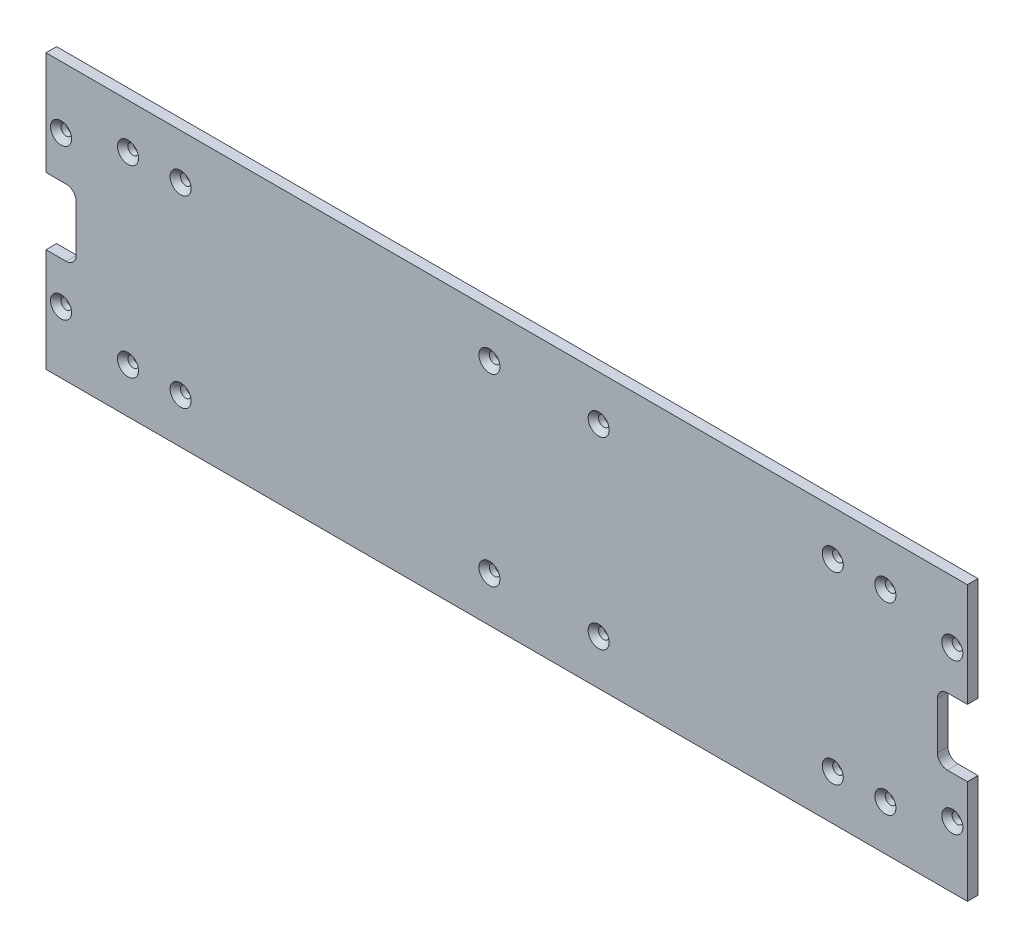
SolidWorks part; units mm, degrees
ref_plane "Plan de face" through (0, 0, 0) normal (0, 0, 1) x (1, 0, 0)
ref_plane "Plan de dessus" through (0, 0, 0) normal (0, 1, 0) x (1, 0, 0)
ref_plane "Plan de droite" through (0, 0, 0) normal (1, 0, 0) x (0, 0, -1)
sketch "Esquisse1" plane through (0, 0, 0) normal (0, 0, 1) x (1, 0, 0)
  line L1 (13, -10) -> (13, -41) construction
  line L3 (7, 10) -> (13, 10) construction
  line L4 (13, 10) -> (13, 41) construction
  line L5 (-262.5, -21.5723) -> (-262.5, -41) construction
  line L6 (-262.8302, -10) -> (-256.5, -10) construction
  line L8 (-256.5, 10) -> (-262.5, 10) construction
  line L9 (-262.5, 10) -> (-262.5, 41) construction
  line L10 (-262.5, 10) -> (-262.5, 41)
  line L11 (-253.5, 10) -> (-262.5, 10)
  line L12 (-253.5, 10) -> (-253.5, -10)
  line L13 (-262.5, -10) -> (-253.5, -10)
  line L14 (-262.5, -10) -> (-262.5, -41)
  line L15 (13, 10) -> (13, 41)
  line L16 (4, 10) -> (13, 10)
  line L17 (4, -10) -> (4, 10)
  line L18 (13, -10) -> (13, -41)
  line L19 (-262.5, -41) -> (13, -41)
  line L20 (13, 41) -> (-262.5, 41)
  line L21 (4, -10) -> (13, -10)
  dimension "D1" = 9
  dimension "D2" = 31
  dimension "D3" = 20
  dimension "D4" = 9
extrude "Boss.-Extru.1" add sketch "Esquisse1" along normal up to surface (3.175 mm away)
hole_wizard "Fraisage pour vis à tête fraisée M31" positions "Esquisse3" profile "Esquisse4" countersink size "M3" standard "Ansi Metric" end condition through all
sketch "Esquisse3" plane through (0, 0, 3.175) normal (0, 0, 1) x (1, 0, 0)
  line L0 (-124.75, 41) -> (-124.75, -41) construction
  line L2 (13, -41) -> (-262.5, -41) construction
  line L4 (4, 0) -> (-124.75, 0) construction
  line L5 (4, 10) -> (4, -10) construction
  point P0 (-11.515, 27.5)
  point P18 (-11.515, -27.5)
  point P19 (-237.985, -27.5)
  point P20 (-237.985, 27.5)
  point P22 (-27.25, 27.5)
  point P50 (-27.25, -27.5)
  point P62 (-222.25, -27.5)
  point P63 (-222.25, 27.5)
  point P64 (-97.25, 27.5)
  point P69 (-97.25, -27.5)
  point P70 (-129.905, 27.5)
  point P75 (-129.905, -27.5)
  dimension "D1" = 55
  dimension "D2" = 226.47
  dimension "D3" = 55
  dimension "D4" = 195
  dimension "D5" = 70
  dimension "D6" = 108.08
sketch "Esquisse4" plane through (-11.515, 27.5, 3.175) normal (1, 0, 0) x (0, -1, 0)
  line L0 (0, 0) -> (0, 3.175)
  line L1 (0, 3.175) -> (1.6, 3.175)
  line L2 (1.6, 3.175) -> (1.6, 1.55)
  line L3 (1.6, 1.55) -> (3.15, 0)
  line L5 (3.15, 0) -> (0, 0)
  line L6 (-1.6, 1.55) -> (-3.15, 0) construction
  line L11 (0, -6.35) -> (0, 107.95) construction
  dimension "Diamètre du perçage jusqu'au prochain" = 3.2
  dimension "Profondeur du perçage jusqu'au prochain" = 3.175
  dimension "Diamètre du fraisage entrant" = 6.3
  dimension "Angle du fraisage entrant" = 90
hole_wizard "Fraisage pour vis à tête fraisée M32" positions "Esquisse5" profile "Esquisse6" countersink size "M3" standard "Ansi Metric" end condition through all
sketch "Esquisse5" plane through (0, 0, 3.175) normal (0, 0, 1) x (1, 0, 0)
  point P0 (8.5, -22.5)
  point P3 (8.5, 22.5)
  point P6 (-258, -22.5)
  point P9 (-258, 22.5)
sketch "Esquisse6" plane through (8.5, -22.5, 3.175) normal (1, 0, 0) x (0, -1, 0)
  line L0 (0, 0) -> (0, 3.175)
  line L1 (0, 3.175) -> (1.6, 3.175)
  line L2 (1.6, 3.175) -> (1.6, 1.55)
  line L3 (1.6, 1.55) -> (3.15, 0)
  line L5 (3.15, 0) -> (0, 0)
  line L6 (-1.6, 1.55) -> (-3.15, 0) construction
  line L11 (0, -6.35) -> (0, 107.95) construction
  dimension "Diamètre du perçage jusqu'au prochain" = 3.2
  dimension "Profondeur du perçage jusqu'au prochain" = 3.175
  dimension "Diamètre du fraisage entrant" = 6.3
  dimension "Angle du fraisage entrant" = 90
fillet "Congé1" radius 3 4 edges at (4, -10, 1.5875) (4, 10, 1.5875) (-253.5, -10, 1.5875) (-253.5, 10, 1.5875)
